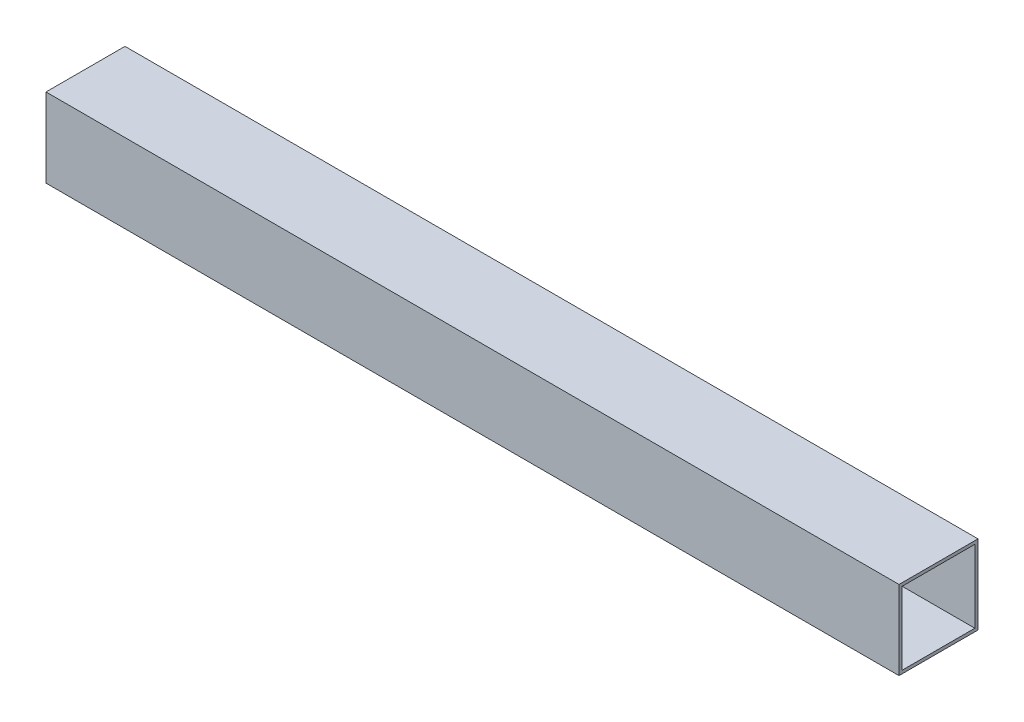
SolidWorks part; units mm, degrees
ref_plane "Front Plane" through (0, 0, 0) normal (0, 0, 1) x (1, 0, 0)
ref_plane "Top Plane" through (0, 0, 0) normal (0, 1, 0) x (1, 0, 0)
ref_plane "Right Plane" through (0, 0, 0) normal (1, 0, 0) x (0, 0, -1)
sketch "Sketch2" plane through (0, 0, 0) normal (1, 0, 0) x (0, 0, -1)
  line L1 (12.5, -12.5) -> (-12.5, -12.5)
  line L2 (12.5, -12.5) -> (12.5, 12.5)
  line L3 (12.5, 12.5) -> (-12.5, 12.5)
  line L4 (-12.5, -12.5) -> (-12.5, 12.5)
  line L5 (12.5, -12.5) -> (-12.5, 12.5) construction
  line L6 (12.5, 12.5) -> (-12.5, -12.5) construction
  line L7 (11.5, -11.5) -> (-11.5, -11.5)
  line L8 (11.5, -11.5) -> (11.5, 11.5)
  line L9 (11.5, 11.5) -> (-11.5, 11.5)
  line L10 (-11.5, -11.5) -> (-11.5, 11.5)
  line L11 (11.5, -11.5) -> (-11.5, 11.5) construction
  line L12 (11.5, 11.5) -> (-11.5, -11.5) construction
  point P0 (0, 0)
  point P7 (0, 0)
  dimension "D1" = 25
  dimension "D2" = 1
extrude "Boss-Extrude1" add sketch "Sketch2" along normal blind 270
